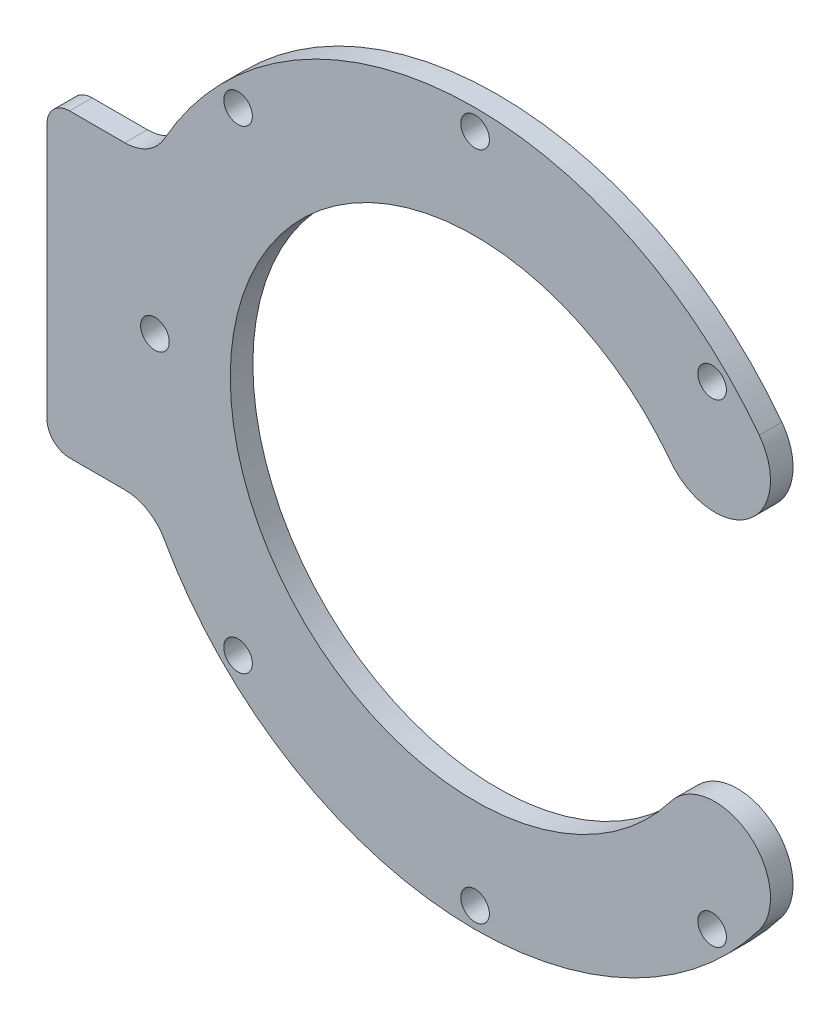
SolidWorks part; units mm, degrees
ref_plane "前视基准面" through (0, 0, 0) normal (0, 0, 1) x (1, 0, 0)
ref_plane "上视基准面" through (0, 0, 0) normal (0, 1, 0) x (1, 0, 0)
ref_plane "右视基准面" through (0, 0, 0) normal (1, 0, 0) x (0, 0, -1)
other "Configuration Table"
sketch "草图1" plane through (0, 0, 0) normal (0, 0, 1) x (1, 0, 0)
  circle A0 centre (0, 0) radius 44.5 construction
  circle A1 centre (0, 0) radius 42.5 construction
  circle A2 centre (0, 0) radius 47.25
  circle A3 centre (0, 0) radius 32.5
  circle A4 centre (0, 44.5) radius 1.9
  circle A5 centre (0, 42.5) radius 1.9
  circle A6 centre (30.052, 30.052) radius 1.9
  circle A7 centre (31.4663, 31.4663) radius 1.9
  circle A8 centre (42.5, 0) radius 1.9
  circle A9 centre (44.5, 0) radius 1.9
  circle A10 centre (30.052, -30.052) radius 1.9
  circle A11 centre (31.4663, -31.4663) radius 1.9
  circle A12 centre (0, -42.5) radius 1.9
  circle A13 centre (0, -44.5) radius 1.9
  circle A14 centre (-30.052, -30.052) radius 1.9
  circle A15 centre (-31.4663, -31.4663) radius 1.9
  circle A16 centre (-42.5, 0) radius 1.9
  circle A17 centre (-44.5, 0) radius 1.9
  circle A18 centre (-30.052, 30.052) radius 1.9
  circle A19 centre (-31.4663, 31.4663) radius 1.9
  point P41 (0, 0)
  dimension "D1" = 85
  dimension "D2" = 89
  dimension "D3" = 94.5
  dimension "D4" = 65
  dimension "D5" = 3.8
  dimension "D8" = 42.5
  dimension "D7" = 45
  dimension "D6" = 8
extrude "凸台-拉伸1" add sketch "草图1" along normal blind 3 contours A2 A19 A18 A17 A16 A15 A14 A13 A12 A11 A10 A9 A8 A7 A6 A5 A4 A3 | A16 A17 | A8 A9 | A7 A6 | A4 A5 | A19 A18 | A15 A14 | A13 A12 | A11 A10
sketch "草图2" plane through (0, 0, 3) normal (0, 0, 1) x (1, 0, 0)
  line L0 (-47.25, 0) -> (47.25, 0) construction
  circle A0 centre (0, 0) radius 32.5 construction
  circle A1 centre (0, 0) radius 47.25 construction
  circle A2 centre (0, 0) radius 32.5
  circle A3 centre (0, 0) radius 47.25
  circle A4 centre (31.8436, 24) radius 7.375
  circle A5 centre (31.8436, -24) radius 7.375
  circle M11 centre (42.5, 0) radius 1.9
  circle M14 centre (0, 0) radius 32.5
  circle M15 centre (0, 0) radius 47.25
  dimension "D1" = 48
extrude "切除-拉伸1" cut sketch "草图2" against normal blind 3 contours L0 A4 M14 M11 M15 | L0 A2 A5 A3 M11
sketch "草图3" plane through (0, 0, 3) normal (0, 0, 1) x (1, 0, 0)
  line L0 (-56.8318, 19.95) -> (-56.8318, -19.95)
  line L1 (-56.8318, 0) -> (0, 0) construction
  line L2 (-56.8318, 19.95) -> (-42.8318, 19.95)
  line L4 (-56.8318, -19.95) -> (-42.8318, -19.95)
  arc A0 (37.7332, 28.4389) -> (37.7332, -28.4389) centre (0, 0) ccw construction
  arc A1 (37.7332, 28.4389) -> (37.7332, -28.4389) centre (0, 0) ccw
  arc A6 (25.954, 19.5611) -> (25.954, -19.5611) centre (0, 0) ccw
  arc A7 (25.954, 19.5611) -> (37.7332, 28.4389) centre (31.8436, 24) ccw
  arc A8 (37.7332, 28.4389) -> (37.7332, -28.4389) centre (0, 0) ccw
  arc A9 (37.7332, -28.4389) -> (25.954, -19.5611) centre (31.8436, -24) ccw
  arc A10 (25.954, 19.5611) -> (25.954, -19.5611) centre (0, 0) ccw
  arc A11 (25.954, 19.5611) -> (37.7332, 28.4389) centre (31.8436, 24) ccw
  arc A12 (37.7332, 28.4389) -> (37.7332, -28.4389) centre (0, 0) ccw
  arc A13 (37.7332, -28.4389) -> (25.954, -19.5611) centre (31.8436, -24) ccw
  arc M12 (37.7332, 28.4389) -> (37.7332, -28.4389) centre (0, 0) ccw
  dimension "D1" = 39.9
  dimension "D2" = 47.25
  dimension "D3" = 14
  dimension "D4" = 0
extrude "凸台-拉伸2" add sketch "草图3" against normal blind 3 contours L0 L1 L2 M12 | L1 L0 L4 A12
fillet "圆角1" radius 3 2 edges at (-56.8318, -19.95, 1.5) (-56.8318, 19.95, 1.5)
fillet "圆角2" radius 6 2 edges at (-42.8318, -19.95, 1.5) (-42.8318, 19.95, 1.5)
